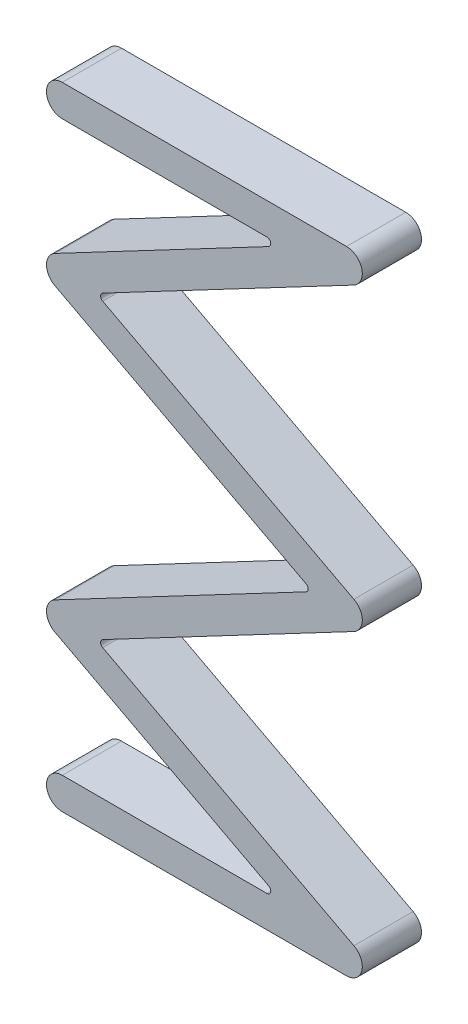
SolidWorks part; units mm, degrees
ref_plane "Front Plane" through (0, 0, 0) normal (0, 0, 1) x (1, 0, 0)
ref_plane "Top Plane" through (0, 0, 0) normal (0, 1, 0) x (1, 0, 0)
ref_plane "Right Plane" through (0, 0, 0) normal (1, 0, 0) x (0, 0, -1)
sketch "Sketch2" plane through (0, 0, 0) normal (0, 0, 1) x (1, 0, 0)
  line L0 (0.4, 0.4) -> (7.6, 0.4) construction
  line L1 (0, 0) -> (8, 0) construction
  line L2 (0, 0) -> (0, 16) construction
  line L3 (0, 16) -> (8, 16) construction
  line L4 (8, 0) -> (8, 16) construction
  line L5 (0.4, 15.6) -> (7.6, 15.6) construction
  line L6 (7.6, 15.6) -> (0.4, 11.8) construction
  line L7 (0.4, 11.8) -> (7.6, 8) construction
  line L8 (7.6, 8) -> (0.4, 4.2) construction
  line L9 (0.4, 4.2) -> (7.6, 0.4) construction
  line L10 (0.4, 15.2) -> (5.9851, 15.2)
  line L11 (5.9851, 15.2) -> (-0.457, 11.8)
  line L12 (-0.457, 11.8) -> (6.743, 8)
  line L13 (6.743, 8) -> (-0.457, 4.2)
  line L14 (-0.457, 4.2) -> (5.9851, 0.8)
  line L15 (0.4, 0.8) -> (5.9851, 0.8)
  line L16 (0.4, 16) -> (9.2149, 16)
  line L17 (9.2149, 16) -> (1.257, 11.8)
  line L18 (1.257, 11.8) -> (8.457, 8)
  line L19 (8.457, 8) -> (1.257, 4.2)
  line L20 (1.257, 4.2) -> (9.2149, 0)
  line L21 (0.4, 0) -> (9.2149, 0)
  line L23 (0.4, 4.2) -> (1.257, 4.2) construction
  arc A0 (0.4, 15.2) -> (0.4, 16) centre (0.4, 15.6) cw
  arc A1 (0.4, 0.8) -> (0.4, 0) centre (0.4, 0.4) ccw
  point P9 (7.6, 8)
  dimension "D1" = 16
  dimension "D2" = 8
  dimension "D3" = 0.4
  dimension "D4" = 0.4
  dimension "D5" = 0.4
  dimension "D7" = 0.4
  dimension "D8" = 0.4
  dimension "D9" = 0.4
extrude "Boss-Extrude1" add sketch "Sketch2" along normal blind 1.5
fillet "Fillet1" radius 0.4 5 edges at (9.2149, 0, 0.75) (8.457, 8, 0.75) (9.2149, 16, 0.75) (-0.457, 11.8, 0.75) (-0.457, 4.2, 0.75)
fillet "Fillet2" radius 0.1 5 edges at (5.9851, 0.8, 0.75) (1.257, 4.2, 0.75) (1.257, 11.8, 0.75) (6.743, 8, 0.75) (5.9851, 15.2, 0.75)
